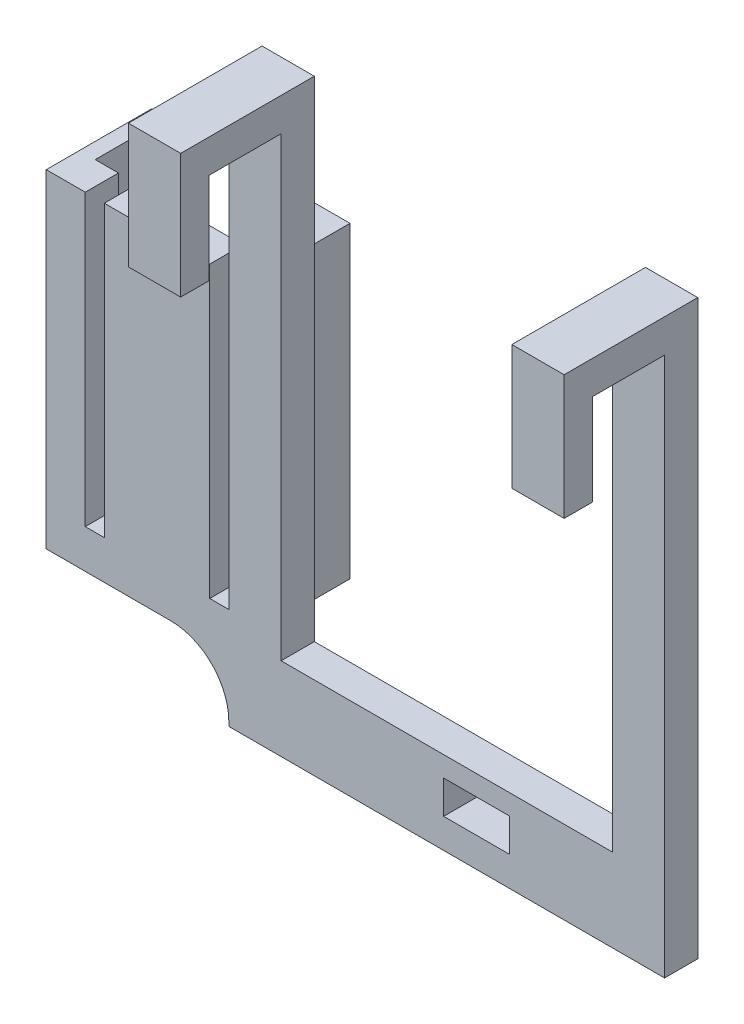
SolidWorks part; units mm, degrees
ref_plane "Спереди" through (0, 0, 0) normal (0, 0, 1) x (1, 0, 0)
ref_plane "Сверху" through (0, 0, 0) normal (0, 1, 0) x (1, 0, 0)
ref_plane "Справа" through (0, 0, 0) normal (1, 0, 0) x (0, 0, -1)
sketch "Эскиз1" plane through (0, 0, 0) normal (0, 0, 1) x (1, 0, 0)
  line L0 (26.25, 0) -> (26.25, 10) construction
  line L1 (0, 0) -> (52.5, 0)
  line L2 (0, 0) -> (0, 10)
  line L3 (0, 10) -> (52.5, 10)
  line L4 (52.5, 0) -> (52.5, 10)
  line L5 (0, 10) -> (6.3, 10)
  line L6 (0, 10) -> (0, 69)
  line L7 (0, 69) -> (6.3, 69)
  line L8 (6.3, 10) -> (6.3, 69)
  line L9 (26.25, 10) -> (26.25, 0) construction
  line L10 (46.2, 10) -> (46.2, 69)
  line L11 (52.5, 10) -> (52.5, 69)
  line L12 (52.5, 69) -> (46.2, 69)
  dimension "D1" = 52.5
  dimension "D2" = 10
  dimension "D3" = 59
  dimension "D4" = 6.3
extrude "Бобышка-Вытянуть1" add sketch "Эскиз1" along normal blind 4 contours L3 L8 L7 L6 | L1 L4 L3 L2 | L11 L12 L10 L3
sketch "Эскиз2" plane through (0, 0, 4) normal (0, 0, 1) x (1, 0, 0)
  line L0 (6.3, 10) -> (6.3, 69) construction
  line L1 (0, 69) -> (6.3, 69)
  line L2 (0, 69) -> (0, 65)
  line L3 (0, 65) -> (6.3, 65)
  line L4 (6.3, 69) -> (6.3, 65)
  line L5 (26.25, 0) -> (26.25, 10) construction
  line L6 (0, 0) -> (52.5, 0) construction
  line L7 (6.3, 10) -> (46.2, 10) construction
  line L8 (52.5, 65) -> (46.2, 65)
  line L9 (46.2, 69) -> (46.2, 65)
  line L10 (52.5, 69) -> (52.5, 65)
  line L11 (52.5, 69) -> (46.2, 69)
  dimension "D1" = 4
extrude "Бобышка-Вытянуть2" add sketch "Эскиз2" along normal blind 12.1
sketch "Эскиз3" plane through (0, 65, 0) normal (0, -1, 0) x (1, 0, 0)
  line L0 (46.2, 16.1) -> (46.2, 4) construction
  line L1 (52.5, 16.1) -> (46.2, 16.1)
  line L2 (52.5, 16.1) -> (52.5, 12.7)
  line L3 (52.5, 12.7) -> (46.2, 12.7)
  line L4 (46.2, 16.1) -> (46.2, 12.7)
  dimension "D1" = 3.4
extrude "Бобышка-Вытянуть3" add sketch "Эскиз3" along normal blind 11
sketch "Эскиз4" plane through (0, 65, 0) normal (0, -1, 0) x (1, 0, 0)
  line L0 (6.3, 16.1) -> (6.3, 4) construction
  line L1 (0, 16.1) -> (6.3, 16.1)
  line L2 (0, 16.1) -> (0, 12.7)
  line L3 (0, 12.7) -> (6.3, 12.7)
  line L4 (6.3, 16.1) -> (6.3, 12.7)
  dimension "D1" = 3.4
extrude "Бобышка-Вытянуть4" add sketch "Эскиз4" along normal blind 11
sketch "Эскиз5" plane through (0, 0, 0) normal (-1, 0, 0) x (0, 0, 1)
  line L0 (0, 0) -> (0, 69) construction
  line L1 (0, 7.5223) -> (4, 7.5223)
  line L2 (0, 7.5223) -> (0, 47.0972)
  line L3 (0, 47.0972) -> (4, 47.0972)
  line L4 (4, 7.5223) -> (4, 47.0972)
  line L5 (4, 0) -> (4, 65) construction
  point P8 (4, 47.0972)
extrude "Бобышка-Вытянуть5" add sketch "Эскиз5" along normal blind 22
sketch "Эскиз6" plane through (0, 0, 0) normal (0, 0, -1) x (-1, 0, 0)
  line L0 (22, 47.0972) -> (0, 47.0972) construction
  line L5 (8.65, 47.0972) -> (8.65, 7.5223) construction
  line L6 (22, 7.5223) -> (0, 7.5223) construction
  line L11 (0, 49.2) -> (2.3, 49.2)
  line L12 (17.3, 12.2) -> (15, 12.2)
  line L13 (17.3, 12.2) -> (17.3, 49.2)
  line L14 (17.3, 49.2) -> (15, 49.2)
  line L15 (15, 12.2) -> (15, 49.2)
  line L16 (0, 12.2) -> (0, 49.2)
  line L17 (0, 12.2) -> (2.3, 12.2)
  line L18 (2.3, 12.2) -> (2.3, 49.2)
  line L19 (0, 63.4297) -> (0, 7.5223) construction
  line L20 (0, 47.0972) -> (0, 69) construction
  dimension "D1" = 12.7
  dimension "D2" = 2.3
  dimension "D3" = 37
  dimension "D4" = 0
extrude "Вырез-Вытянуть1" cut sketch "Эскиз6" against normal through all
fillet "Скругление1" radius 7 1 edges at (0, 7.5223, 2)
sketch "Эскиз7" plane through (0, 0, 4) normal (0, 0, 1) x (1, 0, 0)
  line L1 (25.8828, 3.5601) -> (33.7928, 3.5601)
  line L2 (25.8828, 3.5601) -> (25.8828, 7.5601)
  line L3 (25.8828, 7.5601) -> (33.7928, 7.5601)
  line L4 (33.7928, 3.5601) -> (33.7928, 7.5601)
  point P4 (0, 0)
  point P5 (0, 0)
  point P6 (15.5585, 7.2196)
  point P7 (7.696, 1.4152)
  point P8 (15.6955, 7.225)
  point P9 (0, 0)
  point P10 (0, 0)
  dimension "D1" = 7.91
  dimension "D2" = 4
extrude "Вырез-Вытянуть2" cut sketch "Эскиз7" against normal through all
sketch "Эскиз8" plane through (0, 0, 4) normal (0, 0, 1) x (1, 0, 0)
  line L0 (-22, 7.5223) -> (-7, 7.5223) construction
  line L1 (-22, 47.0972) -> (-20.1, 47.0972)
  line L2 (-22, 47.0972) -> (-22, 7.5223)
  line L3 (-22, 7.5223) -> (-20.1, 7.5223)
  line L4 (-20.1, 47.0972) -> (-20.1, 7.5223)
  line L6 (0, 10) -> (1.9, 10)
  line L7 (0, 10) -> (0, 47.0972)
  line L8 (0, 47.0972) -> (1.9, 47.0972)
  line L9 (1.9, 10) -> (1.9, 47.0972)
  dimension "D1" = 1.9
  dimension "D2" = 1.9
extrude "Бобышка-Вытянуть6" add sketch "Эскиз8" against normal blind 12.7
sketch "Эскиз9" plane through (-20.1, 0, 0) normal (1, 0, 0) x (0, 0, -1)
  line L0 (8.7, 47.0972) -> (0, 47.0972) construction
  line L1 (8.7, 7.5223) -> (5.7, 7.5223)
  line L2 (8.7, 7.5223) -> (8.7, 47.0972)
  line L3 (8.7, 47.0972) -> (5.7, 47.0972)
  line L4 (5.7, 7.5223) -> (5.7, 47.0972)
  dimension "D1" = 3
extrude "Бобышка-Вытянуть7" add sketch "Эскиз9" along normal blind 3.5
sketch "Эскиз10" plane through (0, 0, 0) normal (-1, 0, 0) x (0, 0, 1)
  line L0 (-8.7, 47.0972) -> (0, 47.0972) construction
  line L1 (-8.7, 10) -> (-5.7, 10)
  line L2 (-8.7, 10) -> (-8.7, 47.0972)
  line L3 (-8.7, 47.0972) -> (-5.7, 47.0972)
  line L4 (-5.7, 10) -> (-5.7, 47.0972)
  dimension "D1" = 3
extrude "Бобышка-Вытянуть8" add sketch "Эскиз10" along normal blind 3.5
